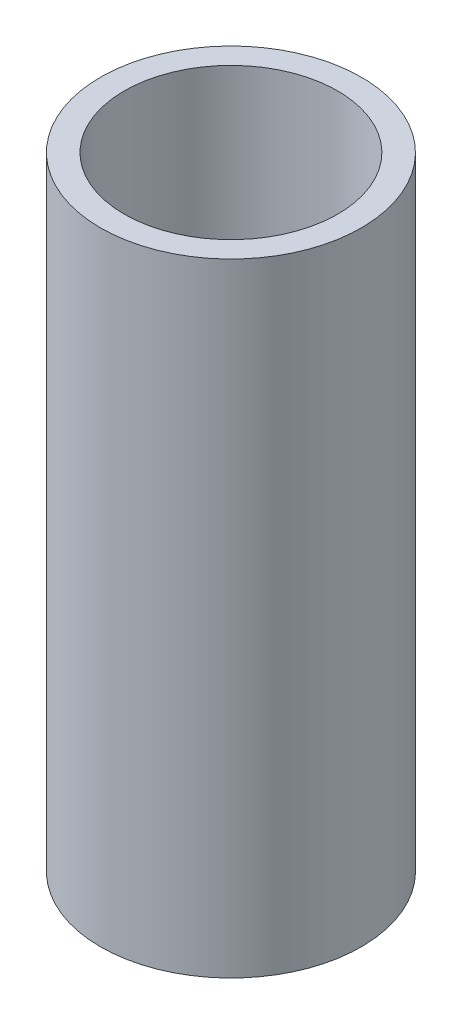
SolidWorks part; units mm, degrees
ref_plane "Front Plane" through (0, 0, 0) normal (0, 0, 1) x (1, 0, 0)
ref_plane "Top Plane" through (0, 0, 0) normal (0, 1, 0) x (1, 0, 0)
ref_plane "Right Plane" through (0, 0, 0) normal (1, 0, 0) x (0, 0, -1)
sketch "Sketch1" plane through (0, 0, 0) normal (0, 1, 0) x (1, 0, 0)
  circle A0 centre (0, 0) radius 2.0955
  circle A1 centre (0, 0) radius 1.7145
extrude "Boss-Extrude1" add sketch "Sketch1" along normal blind 10
